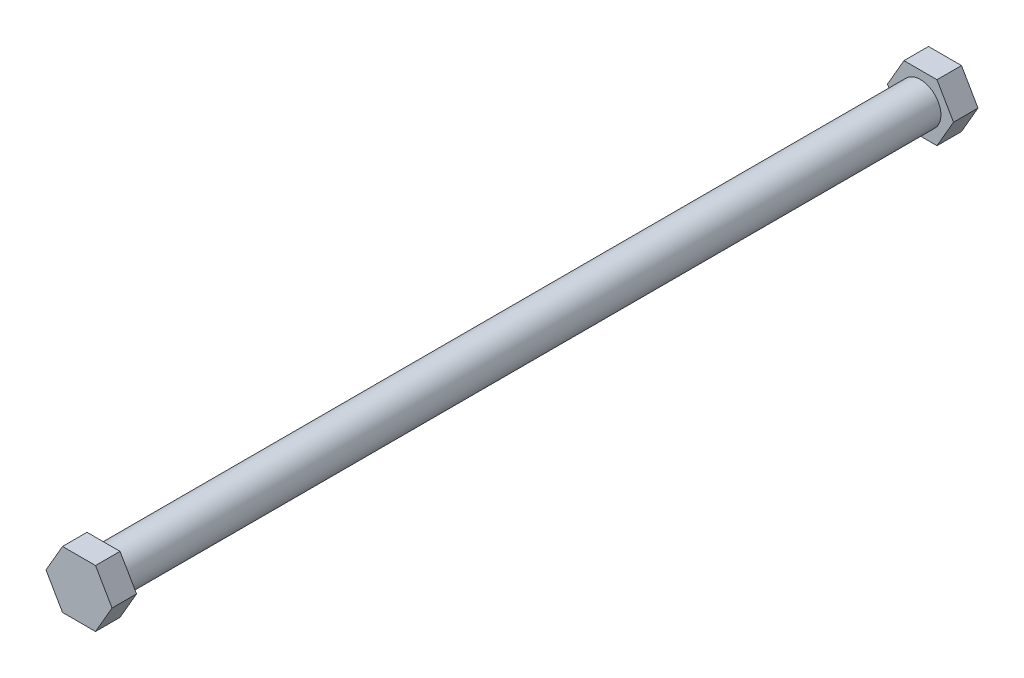
SolidWorks part; units mm, degrees
ref_plane "前基準面" through (0, 0, 0) normal (0, 0, 1) x (1, 0, 0)
ref_plane "上基準面" through (0, 0, 0) normal (0, 1, 0) x (1, 0, 0)
ref_plane "右基準面" through (0, 0, 0) normal (1, 0, 0) x (0, 0, -1)
sketch "草圖1" plane through (0, 0, 0) normal (0, 0, 1) x (1, 0, 0)
  circle A0 centre (0, 0) radius 2.5
  dimension "D1" = 5
extrude "填料-伸長1" add sketch "草圖1" along normal blind 100
sketch "草圖2" plane through (0, 0, 0) normal (0, 0, 1) x (1, 0, 0)
  line L1 (4.0415, 0) -> (2.0207, 3.5)
  line L2 (2.0207, 3.5) -> (-2.0207, 3.5)
  line L3 (-2.0207, 3.5) -> (-4.0415, 0)
  line L4 (-4.0415, 0) -> (-2.0207, -3.5)
  line L5 (-2.0207, -3.5) -> (2.0207, -3.5)
  line L6 (2.0207, -3.5) -> (4.0415, 0)
  circle A0 centre (0, 0) radius 3.5 construction
  dimension "D1" = 7
sketch "草圖3" plane through (0, 0, 0) normal (0, 0, 1) x (1, 0, 0)
  line L0 (2.0207, 3.5) -> (-2.0207, 3.5) construction
  line L1 (-2.0207, 3.5) -> (-4.0415, 0) construction
  line L2 (-4.0415, 0) -> (-2.0207, -3.5) construction
  line L3 (-2.0207, -3.5) -> (2.0207, -3.5) construction
  line L4 (2.0207, -3.5) -> (4.0415, 0) construction
  line L5 (4.0415, 0) -> (2.0207, 3.5) construction
  line L6 (2.0207, 3.5) -> (-2.0207, 3.5)
  line L7 (-2.0207, 3.5) -> (-4.0415, 0)
  line L8 (-4.0415, 0) -> (-2.0207, -3.5)
  line L9 (-2.0207, -3.5) -> (2.0207, -3.5)
  line L10 (2.0207, -3.5) -> (4.0415, 0)
  line L11 (4.0415, 0) -> (2.0207, 3.5)
extrude "填料-伸長2" add sketch "草圖3" against normal blind 3
sketch "草圖4" plane through (0, 0, 0) normal (0, 0, 1) x (1, 0, 0)
  line L0 (-4.0415, 0) -> (-2.0207, -3.5) construction
  line L1 (-2.0207, -3.5) -> (2.0207, -3.5) construction
  line L2 (2.0207, -3.5) -> (4.0415, 0) construction
  line L3 (4.0415, 0) -> (2.0207, 3.5) construction
  line L4 (2.0207, 3.5) -> (-2.0207, 3.5) construction
  line L5 (-2.0207, 3.5) -> (-4.0415, 0) construction
  line L6 (-4.0415, 0) -> (-2.0207, -3.5)
  line L7 (-2.0207, -3.5) -> (2.0207, -3.5)
  line L8 (2.0207, -3.5) -> (4.0415, 0)
  line L9 (4.0415, 0) -> (2.0207, 3.5)
  line L10 (2.0207, 3.5) -> (-2.0207, 3.5)
  line L11 (-2.0207, 3.5) -> (-4.0415, 0)
extrude "填料-伸長3" add sketch "草圖4" along normal blind 3 from surface at 100 starting at face at (2.5, 0, 100)
